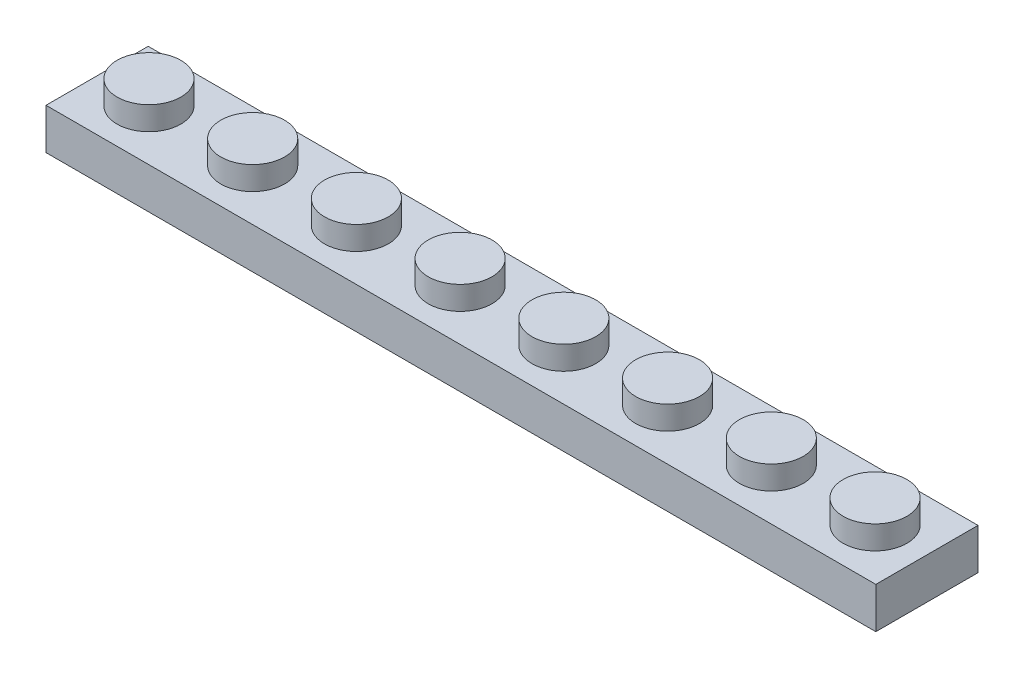
SolidWorks part; units mm, degrees
ref_plane "Front Plane" through (0, 0, 0) normal (0, 0, 1) x (1, 0, 0)
ref_plane "Top Plane" through (0, 0, 0) normal (0, 1, 0) x (1, 0, 0)
ref_plane "Right Plane" through (0, 0, 0) normal (1, 0, 0) x (0, 0, -1)
sketch "Sketch2" plane through (0, 0, 0) normal (0, 1, 0) x (1, 0, 0)
  line L1 (-31.875, 3.925) -> (31.875, 3.925)
  line L2 (-31.875, 3.925) -> (-31.875, -3.925)
  line L3 (-31.875, -3.925) -> (31.875, -3.925)
  line L4 (31.875, 3.925) -> (31.875, -3.925)
  line L5 (-31.875, 3.925) -> (31.875, -3.925) construction
  line L6 (-31.875, -3.925) -> (31.875, 3.925) construction
  point P0 (0, 0)
  dimension "D1" = 7.85
  dimension "D2" = 63.75
extrude "Boss-Extrude1" add sketch "Sketch2" against normal blind 3.15
sketch "Sketch3" plane through (0, 0, 0) normal (0, 1, 0) x (1, 0, 0)
  line L1 (-31.875, 3.925) -> (-31.875, -3.925) construction
  line L2 (-31.875, -3.925) -> (31.875, -3.925) construction
  circle A0 centre (-27.8906, 0) radius 2.45
  circle A1 centre (-19.9219, 0) radius 2.45
  circle A2 centre (-11.9531, 0) radius 2.45
  circle A3 centre (-3.9844, 0) radius 2.45
  circle A4 centre (3.9844, 0) radius 2.45
  circle A5 centre (11.9531, 0) radius 2.45
  circle A6 centre (19.9219, 0) radius 2.45
  circle A7 centre (27.8906, 0) radius 2.45
  dimension "D1" = 4.9
  dimension "D5" = 7.9688
  dimension "D2" = 3.9844
  dimension "D3" = 3.925
  dimension "D4" = 8
extrude "Boss-Extrude2" add sketch "Sketch3" along normal blind 1.8
shell "Shell1" thickness 1.5
sketch "Sketch4" plane through (0, -1.5, 0) normal (0, -1, 0) x (1, 0, 0)
  line L1 (-31.875, -3.925) -> (-31.875, 3.925) construction
  line L3 (31.875, -3.925) -> (-31.875, -3.925) construction
  circle A0 centre (-23.9063, 0) radius 1.5
  circle A1 centre (-23.9063, 0) radius 0.8
  circle A2 centre (-15.9375, 0) radius 1.5
  circle A3 centre (-15.9375, 0) radius 0.8
  circle A4 centre (-7.9688, 0) radius 1.5
  circle A5 centre (-7.9688, 0) radius 0.8
  circle A6 centre (0, 0) radius 1.5
  circle A7 centre (0, 0) radius 0.8
  circle A8 centre (7.9687, 0) radius 1.5
  circle A9 centre (7.9687, 0) radius 0.8
  circle A10 centre (15.9375, 0) radius 1.5
  circle A11 centre (15.9375, 0) radius 0.8
  circle A12 centre (23.9062, 0) radius 1.5
  circle A13 centre (23.9062, 0) radius 0.8
  dimension "D3" = 3
  dimension "D4" = 1.6
  dimension "D6" = 7.9688
  dimension "D1" = 7.9688
  dimension "D2" = 3.925
  dimension "D5" = 7
extrude "Boss-Extrude3" add sketch "Sketch4" along normal offset from surface (1.45 mm away) 0.2 up to face at (0, -3.15, 0)
